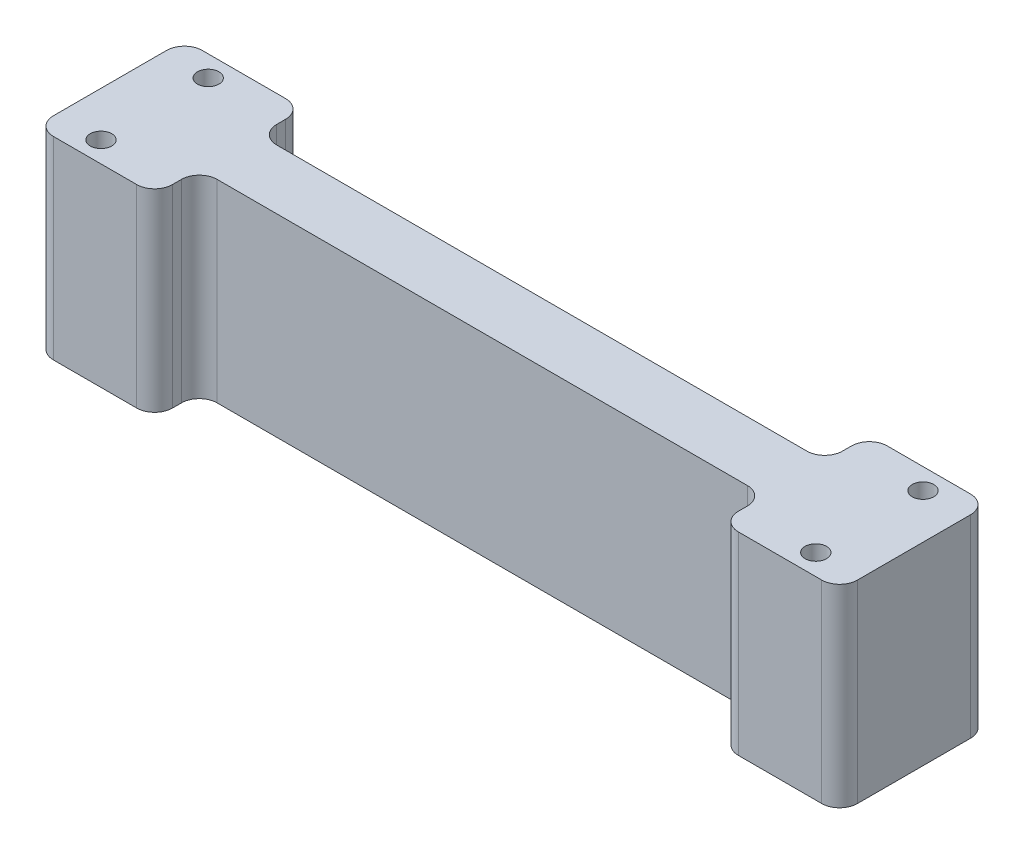
SolidWorks part; units mm, degrees
ref_plane "前视基准面" through (0, 0, 0) normal (0, 0, 1) x (1, 0, 0)
ref_plane "上视基准面" through (0, 0, 0) normal (0, 1, 0) x (1, 0, 0)
ref_plane "右视基准面" through (0, 0, 0) normal (1, 0, 0) x (0, 0, -1)
sketch "草图1" plane through (0, 0, 0) normal (0, 1, 0) x (1, 0, 0)
  line L0 (60, 9) -> (-60, 9) construction
  line L1 (-67.5, -12.5) -> (67.5, -12.5)
  line L2 (-67.5, -12.5) -> (-67.5, 12.5)
  line L3 (-67.5, 12.5) -> (67.5, 12.5)
  line L4 (67.5, -12.5) -> (67.5, 12.5)
  line L5 (-67.5, -12.5) -> (67.5, 12.5) construction
  line L6 (-67.5, 12.5) -> (67.5, -12.5) construction
  line L7 (0, -0.7593) -> (0, -24.5326) construction
  line L8 (0, 0) -> (-47.5, 0) construction
  line L9 (-47.5, -12.5) -> (-47.5, -5)
  line L10 (-47.5, -5) -> (47.5, -5)
  line L11 (47.5, -5) -> (47.5, -12.5)
  line L12 (-47.5, 12.5) -> (-47.5, 5)
  line L13 (0, 0.7593) -> (0, 24.5326) construction
  line L14 (-47.5, 5) -> (47.5, 5)
  line L15 (47.5, 5) -> (47.5, 12.5)
  line L16 (-47.5, -12.5) -> (47.5, -12.5)
  line L17 (-47.5, 12.5) -> (47.5, 12.5)
  circle A0 centre (60, 9) radius 1.8
  circle A1 centre (-60, 9) radius 1.8
  circle A2 centre (-60, -9) radius 1.8
  circle A3 centre (60, -9) radius 1.8
  point P0 (0, 0)
  point P30 (0, 0)
  point P31 (0, 0)
  dimension "D1" = 3.6
  dimension "D2" = 2
  dimension "D4" = 120
  dimension "D5" = 25
  dimension "D6" = 135
  dimension "D7" = 10
  dimension "D8" = 20
  dimension "D3" = 2
extrude "凸台-拉伸1" add sketch "草图1" along normal blind 32.5 contours L15 L14 L12 L3 L2 L1 L9 L10 L11 L4 A3 A2 A1 A0
fillet "圆角1" radius 3 12 edges at (47.5, 16.25, -5) (47.5, 16.25, -12.5) (67.5, 16.25, -12.5) (67.5, 16.25, 12.5) (47.5, 16.25, 12.5) (47.5, 16.25, 5) (-67.5, 16.25, 12.5) (-67.5, 16.25, -12.5) (-47.5, 16.25, 12.5) (-47.5, 16.25, 5) (-47.5, 16.25, -12.5) (-47.5, 16.25, -5)
